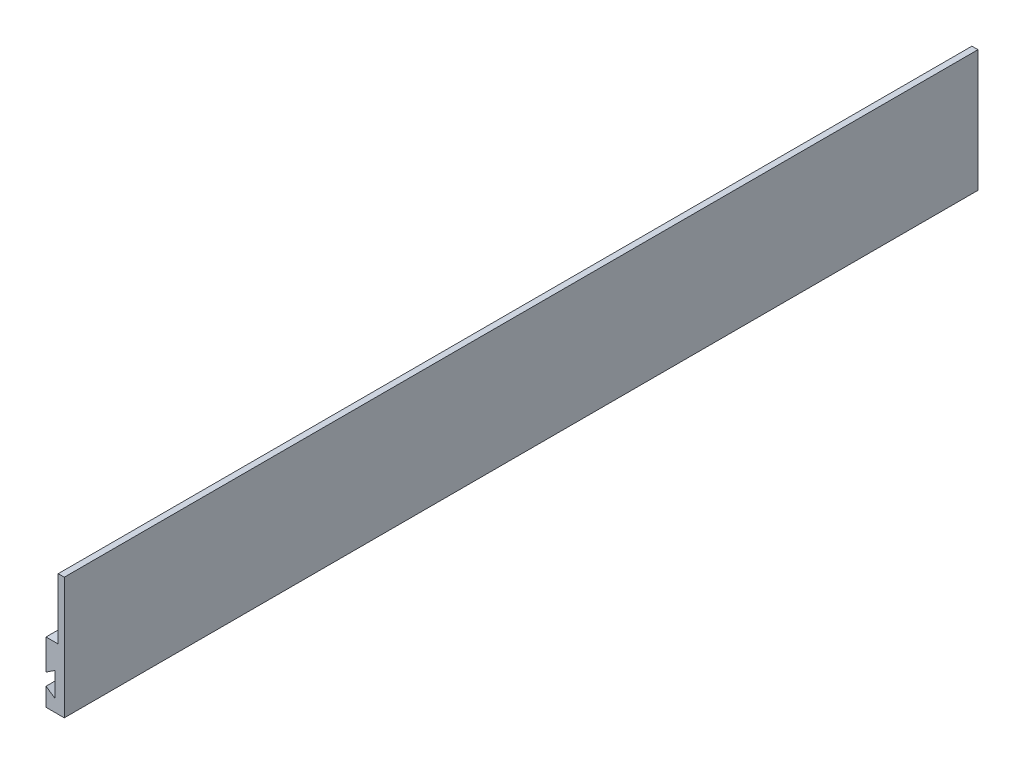
SolidWorks part; units mm, degrees
ref_plane "Front Plane" through (0, 0, 0) normal (0, 0, 1) x (1, 0, 0)
ref_plane "Top Plane" through (0, 0, 0) normal (0, 1, 0) x (1, 0, 0)
ref_plane "Right Plane" through (0, 0, 0) normal (1, 0, 0) x (0, 0, -1)
sketch "Sketch6" plane through (0, 0, 0) normal (0, 0, 1) x (1, 0, 0)
  line L0 (-15, -50) -> (0, -40)
  line L1 (5, 100) -> (15, 100)
  line L2 (-15, 0) -> (-15, -50)
  line L3 (-15, -100) -> (15, -100)
  line L4 (15, 100) -> (15, -100)
  line L5 (0, 0) -> (15, -100) construction
  line L6 (-15, -100) -> (15, 100) construction
  line L9 (-15, 0) -> (5, 0)
  line L10 (5, 100) -> (5, 0)
  line L11 (0, -40) -> (0, -80)
  line L12 (0, -80) -> (-15, -70)
  line L13 (-15, -70) -> (-15, -100)
  point P0 (0, 0)
  point P13 (0, 0)
  point P14 (0, 0)
  point P15 (0, 0)
  point P16 (0, 0)
  point P17 (0, 0)
  point P18 (0, -77.8616)
  point P19 (0, -60)
  point P20 (0, 0)
  point P21 (0, 0)
  dimension "D3" = 100
  dimension "D4" = 20
  dimension "D5" = 30
  dimension "D6" = 50
  dimension "D7" = 40
  dimension "D8" = 20
  dimension "D9" = 15
  dimension "D10" = 40
extrude "Boss-Extrude2" add sketch "Sketch6" along normal blind 1500
